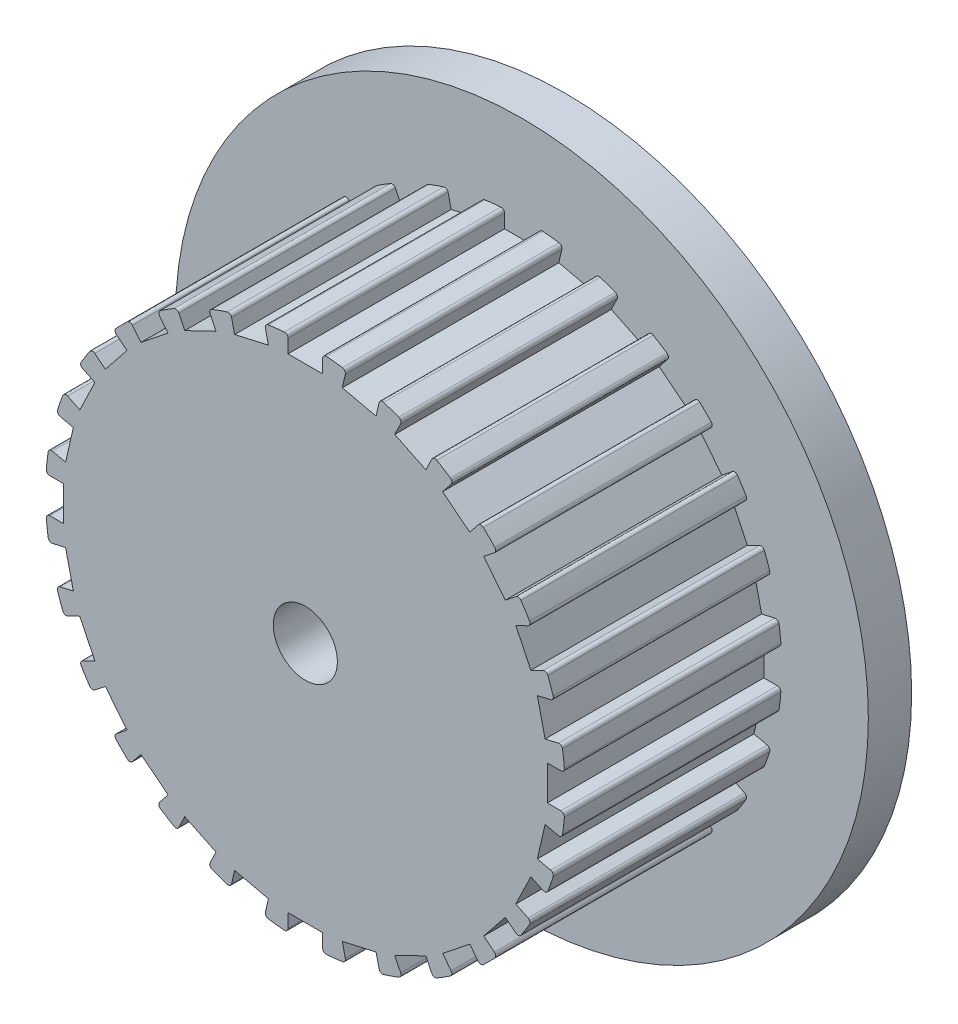
SolidWorks part; units mm, degrees
ref_plane "Front Plane" through (0, 0, 0) normal (0, 0, 1) x (1, 0, 0)
ref_plane "Top Plane" through (0, 0, 0) normal (0, 1, 0) x (1, 0, 0)
ref_plane "Right Plane" through (0, 0, 0) normal (1, 0, 0) x (0, 0, -1)
sketch "Sketch1" plane through (0, 0, 0) normal (0, 0, 1) x (1, 0, 0)
  circle A0 centre (0, 0) radius 12.7
  dimension "D1" = 25.4
extrude "Boss-Extrude1" add sketch "Sketch1" along normal blind 1.5875
sketch "Sketch2" plane through (0, 0, 1.5875) normal (0, 0, 1) x (1, 0, 0)
  circle A0 centre (0, 0) radius 9.525
  dimension "D1" = 19.05
extrude "Boss-Extrude2" add sketch "Sketch2" along normal blind 7.9375
sketch "Sketch3" plane through (0, 0, 9.525) normal (0, 0, 1) x (1, 0, 0)
  circle A0 centre (0, 0) radius 1.175
  dimension "D1" = 2.35
extrude "Cut-Extrude1" cut sketch "Sketch3" against normal through all
sketch "Sketch4" plane through (0, 0, 9.525) normal (0, 0, 1) x (1, 0, 0)
  line L0 (0, 8.8688) -> (0, 9.525) construction
  line L6 (-0.635, 9.5038) -> (0.635, 9.5038)
  line L7 (-0.635, 9.5038) -> (-0.635, 10.1388)
  line L8 (-0.635, 10.1388) -> (0.635, 10.1388)
  line L9 (0.635, 9.5038) -> (0.635, 10.1388)
  line L10 (-0.635, 9.5038) -> (0.635, 9.5038)
  line L11 (-0.635, 9.5038) -> (-0.635, 8.8688)
  line L12 (-0.635, 8.8688) -> (0.635, 8.8688)
  line L13 (0.635, 9.5038) -> (0.635, 8.8688)
  circle A0 centre (0, 0) radius 9.525 construction
  circle A5 centre (0, 0) radius 9.525 construction
  point P13 (0, 9.4966)
  dimension "D1" = 1.27
  dimension "D2" = 0.635
  dimension "D4" = 0.635
extrude "Cut-Extrude2" cut sketch "Sketch4" against normal up to surface (7.9375 mm away) contours L12 L13 L10 L11 | L7 L6 L9 L8 up to face at (9.525, 0, 1.5875)
fillet "Fillet2" radius 0.127 2 edges at (0.635, 9.5038, 5.5563) (-0.635, 9.5038, 5.5563)
pattern_circular "CirPattern1" count 28 over 360 about axis through (0, 0, 0) along (0, 0, 1) of "Cut-Extrude2", "Fillet2"
